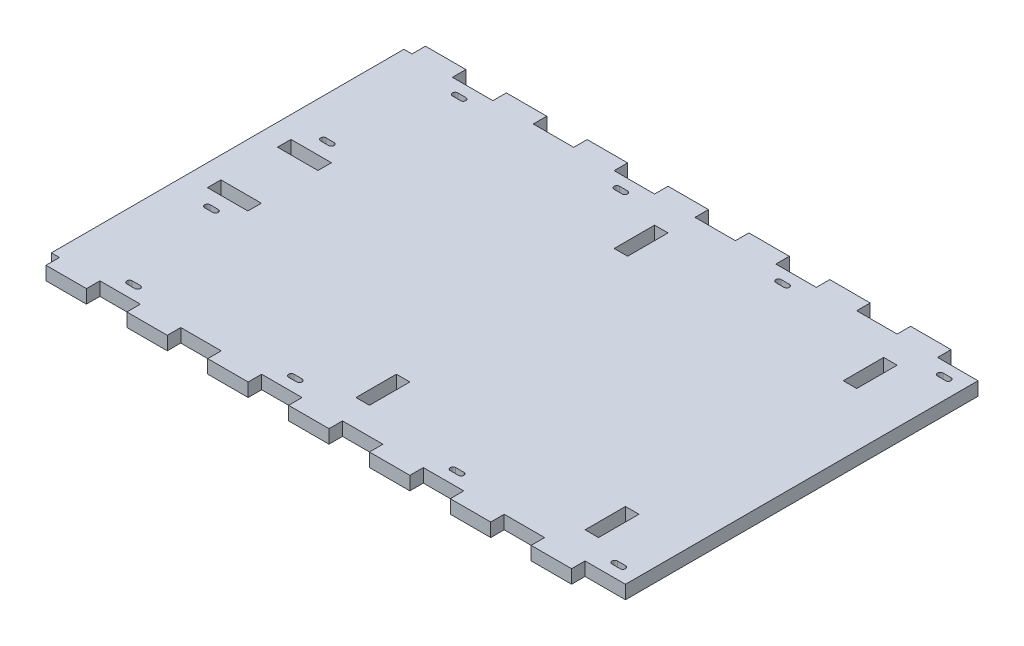
SolidWorks part; units mm, degrees
ref_plane "Front Plane" through (0, 0, 0) normal (0, 0, 1) x (1, 0, 0)
ref_plane "Top Plane" through (0, 0, 0) normal (0, 1, 0) x (1, 0, 0)
ref_plane "Right Plane" through (0, 0, 0) normal (1, 0, 0) x (0, 0, -1)
sketch "Sketch1" plane through (0, 0, 0) normal (0, 1, 0) x (1, 0, 0)
  line L1 (-106.5, -70.395) -> (106.5, -70.395)
  line L2 (-106.5, -70.395) -> (-106.5, 70.395)
  line L3 (-106.5, 70.395) -> (106.5, 70.395)
  line L4 (106.5, -70.395) -> (106.5, 70.395)
  line L5 (-106.5, -70.395) -> (106.5, 70.395) construction
  line L6 (-106.5, 70.395) -> (106.5, -70.395) construction
  point P0 (0, 0)
  dimension "D1" = 213
  dimension "D2" = 140.79
extrude "Boss-Extrude1" add sketch "Sketch1" along normal blind 5
sketch "Sketch2" plane through (0, 0, 0) normal (0, -1, 0) x (1, 0, 0)
  line L0 (-106.5, 70.395) -> (106.5, 70.395) construction
  line L1 (106.5, 70.395) -> (91.5, 70.395)
  line L2 (106.5, 70.395) -> (106.5, 65.395)
  line L3 (106.5, 65.395) -> (91.5, 65.395)
  line L4 (91.5, 70.395) -> (91.5, 65.395)
  line L7 (106.5, 70.395) -> (106.5, -70.395) construction
  dimension "D1" = 15
  dimension "D2" = 5
extrude "Cut-Extrude1" cut sketch "Sketch2" against normal through all
sketch "Sketch5" plane through (0, 0, 0) normal (0, -1, 0) x (1, 0, 0)
  line L0 (100.5, 60.395) -> (97.5, 60.395) construction
  line L1 (100.5, 59.395) -> (97.5, 59.395)
  line L2 (100.5, 61.395) -> (97.5, 61.395)
  line L3 (106.5, 65.395) -> (106.5, -70.395) construction
  line L4 (91.5, 65.395) -> (106.5, 65.395) construction
  arc A0 (100.5, 59.395) -> (100.5, 61.395) centre (100.5, 60.395) ccw
  arc A1 (97.5, 61.395) -> (97.5, 59.395) centre (97.5, 60.395) ccw
  point P2 (99, 60.395)
  dimension "D1" = 2
  dimension "D2" = 3
  dimension "D3" = 7.5
  dimension "D4" = 5
extrude "Cut-Extrude3" cut sketch "Sketch5" against normal through all
pattern_linear "LPattern2" count 4 spacing 60 along (-1, 0, 0) of "Cut-Extrude3"
mirror "Mirror1" about plane through (0, 0, 0) normal (0, 0, 1) of "Cut-Extrude1"
pattern_linear "LPattern1" count 7 spacing 30 along (-1, 0, 0) of "Mirror1", "Cut-Extrude1"
sketch "Sketch3" plane through (0, 0, 0) normal (0, -1, 0) x (1, 0, 0)
  line L0 (1.5, 40.395) -> (1.5, 55.395) construction
  line L1 (1.5, 55.395) -> (-3.5, 55.395) construction
  line L2 (-3.5, 55.395) -> (-3.5, 40.395) construction
  line L3 (-3.5, 40.395) -> (1.5, 40.395) construction
  line L4 (-83.5, 15.5) -> (-98.5, 15.5) construction
  line L5 (-98.5, 15.5) -> (-98.5, 10.5) construction
  line L6 (-98.5, 10.5) -> (-83.5, 10.5) construction
  line L7 (-83.5, 10.5) -> (-83.5, 15.5) construction
  line L12 (-83.5, -10.5) -> (-98.5, -10.5) construction
  line L13 (-98.5, -10.5) -> (-98.5, -15.5) construction
  line L14 (-98.5, -15.5) -> (-83.5, -15.5) construction
  line L15 (-83.5, -15.5) -> (-83.5, -10.5) construction
  line L20 (1.5, -55.395) -> (1.5, -40.395) construction
  line L21 (1.5, -40.395) -> (-3.5, -40.395) construction
  line L22 (-3.5, -40.395) -> (-3.5, -55.395) construction
  line L23 (-3.5, -55.395) -> (1.5, -55.395) construction
  line L24 (81.5, -40.395) -> (81.5, -55.395) construction
  line L25 (81.5, -55.395) -> (86.5, -55.395) construction
  line L26 (86.5, -55.395) -> (86.5, -40.395) construction
  line L27 (86.5, -40.395) -> (81.5, -40.395) construction
  line L28 (81.5, 55.395) -> (81.5, 40.395) construction
  line L29 (81.5, 40.395) -> (86.5, 40.395) construction
  line L30 (86.5, 40.395) -> (86.5, 55.395) construction
  line L31 (86.5, 55.395) -> (81.5, 55.395) construction
  line L32 (1.5, 40.395) -> (1.5, 55.395)
  line L33 (1.5, 55.395) -> (-3.5, 55.395)
  line L34 (-3.5, 55.395) -> (-3.5, 40.395)
  line L35 (-3.5, 40.395) -> (1.5, 40.395)
  line L36 (1.5, -55.395) -> (1.5, -40.395)
  line L37 (1.5, -40.395) -> (-3.5, -40.395)
  line L38 (-3.5, -40.395) -> (-3.5, -55.395)
  line L39 (-3.5, -55.395) -> (1.5, -55.395)
  line L40 (81.5, -40.395) -> (81.5, -55.395)
  line L41 (81.5, -55.395) -> (86.5, -55.395)
  line L42 (86.5, -55.395) -> (86.5, -40.395)
  line L43 (86.5, -40.395) -> (81.5, -40.395)
  line L44 (81.5, 55.395) -> (81.5, 40.395)
  line L45 (81.5, 40.395) -> (86.5, 40.395)
  line L46 (86.5, 40.395) -> (86.5, 55.395)
  line L47 (86.5, 55.395) -> (81.5, 55.395)
  line L176 (-83.5, 15.5) -> (-98.5, 15.5)
  line L177 (-98.5, 15.5) -> (-98.5, 10.5)
  line L178 (-98.5, 10.5) -> (-83.5, 10.5)
  line L179 (-83.5, 10.5) -> (-83.5, 15.5)
  line L180 (-83.5, -10.5) -> (-98.5, -10.5)
  line L181 (-98.5, -10.5) -> (-98.5, -15.5)
  line L182 (-98.5, -15.5) -> (-83.5, -15.5)
  line L183 (-83.5, -15.5) -> (-83.5, -10.5)
extrude "Cut-Extrude2" cut sketch "Sketch3" against normal through all
mirror "Mirror2" about plane through (0, 0, 0) normal (0, 0, 1) of "LPattern2", "Cut-Extrude3"
sketch "Sketch6" plane through (0, 0, 0) normal (0, -1, 0) x (1, 0, 0)
  line L0 (0, 0) -> (-67.6538, 0) construction
  line L1 (-92.5, 21.5) -> (-89.5, 21.5) construction
  line L2 (-92.5, 22.5) -> (-89.5, 22.5)
  line L3 (-92.5, 20.5) -> (-89.5, 20.5)
  line L4 (-91, 21.5) -> (-91, 15.5) construction
  line L5 (-83.5, 15.5) -> (-98.5, 15.5) construction
  line L7 (-92.5, -21.5) -> (-89.5, -21.5) construction
  line L8 (-92.5, -22.5) -> (-89.5, -22.5)
  line L9 (-92.5, -20.5) -> (-89.5, -20.5)
  arc A0 (-92.5, 22.5) -> (-92.5, 20.5) centre (-92.5, 21.5) ccw
  arc A1 (-89.5, 20.5) -> (-89.5, 22.5) centre (-89.5, 21.5) ccw
  arc A2 (-92.5, -22.5) -> (-92.5, -20.5) centre (-92.5, -21.5) cw
  arc A3 (-89.5, -20.5) -> (-89.5, -22.5) centre (-89.5, -21.5) cw
  point P5 (-91, 21.5)
  point P10 (-91, 20.5)
  point P19 (-91, -21.5)
  dimension "D1" = 2
  dimension "D2" = 3
  dimension "D3" = 5
extrude "Cut-Extrude4" cut sketch "Sketch6" against normal through all
sketch "Sketch7" plane through (0, 0, 0) normal (0, -1, 0) x (1, 0, 0)
  line L0 (-88.5, 65.395) -> (-73.5, 65.395) construction
  line L1 (-106.5, 70.395) -> (-103.5, 70.395)
  line L2 (-106.5, 70.395) -> (-106.5, 65.395)
  line L3 (-106.5, 65.395) -> (-103.5, 65.395)
  line L4 (-103.5, 70.395) -> (-103.5, 65.395)
  line L5 (-88.5, 70.395) -> (-88.5, 65.395) construction
  line L6 (0, 0) -> (-44.8525, 0) construction
  line L7 (-103.5, -70.395) -> (-103.5, -65.395)
  line L8 (-106.5, -65.395) -> (-103.5, -65.395)
  line L9 (-106.5, -70.395) -> (-106.5, -65.395)
  line L10 (-106.5, -70.395) -> (-103.5, -70.395)
  dimension "D1" = 15
extrude "Cut-Extrude5" cut sketch "Sketch7" against normal through all
equation "\"D1@Sketch2\"=\"tab_slot_length@ankare 3 linor.Assembly\""
equation "\"D2@Sketch2\"=\"thickness_plates@ankare 3 linor.Assembly\""
